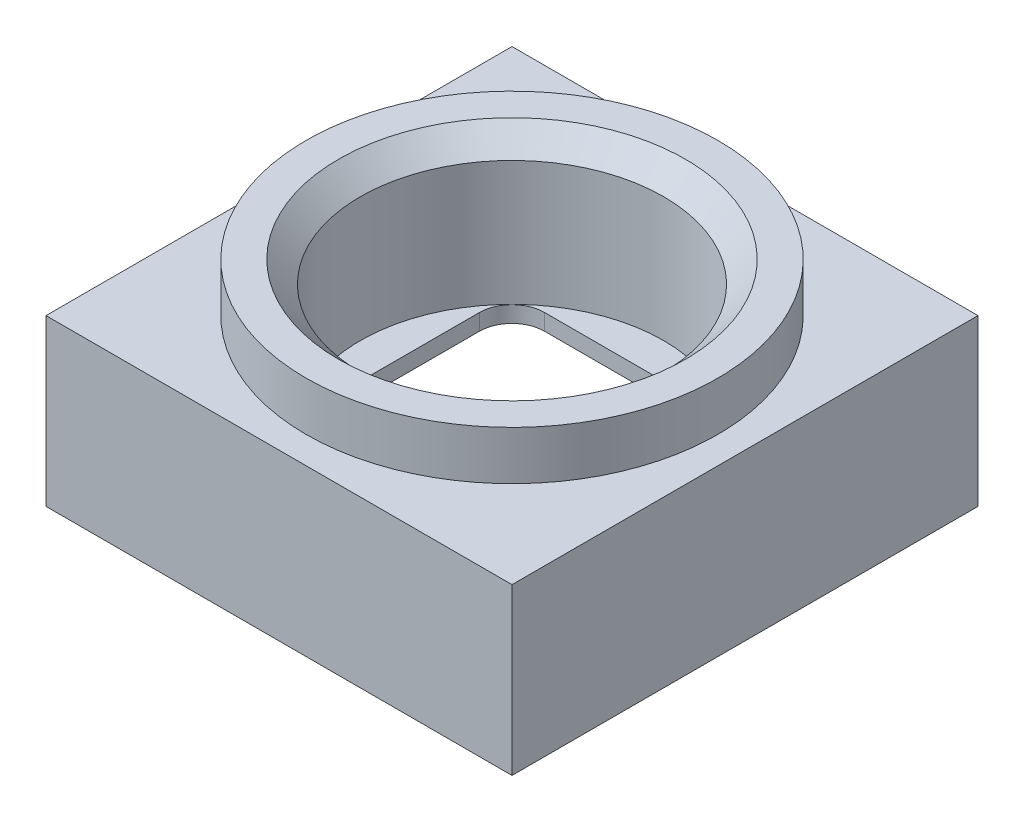
SolidWorks part; units mm, degrees
material "ABS PC"
ref_plane "Vorne" through (0, 0, 0) normal (0, 0, 1) x (1, 0, 0)
ref_plane "Oben" through (0, 0, 0) normal (0, 1, 0) x (1, 0, 0)
ref_plane "Rechts" through (0, 0, 0) normal (1, 0, 0) x (0, 0, -1)
sketch "downside" plane through (0, 0, 0) normal (0, 1, 0) x (1, 0, 0)
  line L0 (-4.3, 4.3) -> (4.3, -4.3) construction
  line L1 (-4.3, 4.3) -> (4.3, 4.3) construction
  line L2 (-4.3, 4.3) -> (-4.3, -4.3) construction
  line L3 (-4.3, -4.3) -> (4.3, -4.3) construction
  line L4 (4.3, 4.3) -> (4.3, -4.3) construction
  dimension "D1" = 8.6
sketch "Skizze2" plane through (0, 0, 0) normal (0, 1, 0) x (1, 0, 0)
  line L0 (-4.3, 4.3) -> (4.3, 4.3) construction
  line L1 (-4.3, 4.3) -> (-4.3, -4.3) construction
  line L2 (4.3, 4.3) -> (4.3, -4.3) construction
  line L3 (-4.3, -4.3) -> (4.3, -4.3) construction
  line L4 (-4.3, 4.3) -> (4.3, 4.3)
  line L5 (-4.3, 4.3) -> (-4.3, -4.3)
  line L6 (4.3, 4.3) -> (4.3, -4.3)
  line L7 (-4.3, -4.3) -> (4.3, -4.3)
  line L8 (-4, 4) -> (4, 4)
  line L9 (4, 4) -> (4, -4)
  line L10 (-4, -4) -> (4, -4)
  line L11 (-4, 4) -> (-4, -4)
  dimension "D1" = 0.3
extrude "Aufsatz-Linear austragen1" add sketch "Skizze2" along normal blind 0.6
sketch "Skizze5" plane through (0, 0.6, 0) normal (0, 1, 0) x (1, 0, 0)
  line L0 (0, 0) -> (0, 3.2) construction
  line L1 (-2.7646, 3.2) -> (2.7646, 3.2)
  line L2 (-2.7646, -3.2) -> (2.7646, -3.2)
  line L3 (-3.2, 2.7646) -> (-3.2, -2.7646)
  line L4 (3.2, 2.7646) -> (3.2, -2.7646)
  line L5 (0, 0) -> (3.2, 0) construction
  line L11 (-4.3, 4.3) -> (-4.3, -4.3)
  line L12 (-4.3, -4.3) -> (4.3, -4.3)
  line L13 (4.3, -4.3) -> (4.3, 4.3)
  line L14 (4.3, 4.3) -> (-4.3, 4.3)
  line L15 (-4.3, 4.3) -> (-4.3, -4.3)
  line L16 (-4.3, -4.3) -> (4.3, -4.3)
  line L17 (4.3, -4.3) -> (4.3, 4.3)
  line L18 (4.3, 4.3) -> (-4.3, 4.3)
  arc A0 (3.2, 2.7646) -> (2.7646, 3.2) centre (3.1, 3.1) ccw
  arc A1 (3.2, -2.7646) -> (2.7646, -3.2) centre (3.1, -3.1) cw
  arc A2 (-3.2, -2.7646) -> (-2.7646, -3.2) centre (-3.1, -3.1) ccw
  arc A3 (-3.2, 2.7646) -> (-2.7646, 3.2) centre (-3.1, 3.1) cw
  point P17 (0, -3.2)
  dimension "D1" = 0.7
  dimension "D2" = 6.4
  dimension "D3" = 0.1
  dimension "D4" = 0
extrude "Aufsatz-Linear austragen3" add sketch "Skizze5" along normal blind 0.35
sketch "Skizze4" plane through (0, 0.95, 0) normal (0, 1, 0) x (1, 0, 0)
  line L0 (0, 2.15) -> (0, -2.15) construction
  line L1 (-1.55, 2.15) -> (1.55, 2.15)
  line L2 (-2.15, 1.55) -> (-2.15, -1.55)
  line L3 (-1.55, -2.15) -> (1.55, -2.15)
  line L4 (2.15, 1.55) -> (2.15, -1.55)
  line L9 (4.3, 4.3) -> (-4.3, 4.3)
  line L10 (-4.3, 4.3) -> (-4.3, -4.3)
  line L11 (-4.3, -4.3) -> (4.3, -4.3)
  line L12 (4.3, -4.3) -> (4.3, 4.3)
  line L13 (4.3, 4.3) -> (-4.3, 4.3)
  line L14 (-4.3, 4.3) -> (-4.3, -4.3)
  line L15 (-4.3, -4.3) -> (4.3, -4.3)
  line L16 (4.3, -4.3) -> (4.3, 4.3)
  arc A0 (-2.15, -1.55) -> (-1.55, -2.15) centre (-1.55, -1.55) ccw
  arc A1 (1.55, -2.15) -> (2.15, -1.55) centre (1.55, -1.55) ccw
  arc A2 (1.55, 2.15) -> (2.15, 1.55) centre (1.55, 1.55) cw
  arc A3 (-1.55, 2.15) -> (-2.15, 1.55) centre (-1.55, 1.55) ccw
  dimension "D1" = 0.6
  dimension "D2" = 4.3
  dimension "D3" = 0
extrude "Aufsatz-Linear austragen2" add sketch "Skizze4" along normal blind 0.3
sketch "Skizze7" plane through (0, 1.25, 0) normal (0, 1, 0) x (1, 0, 0)
  line L4 (4.3, -4.3) -> (4.3, 4.3)
  line L5 (4.3, 4.3) -> (-4.3, 4.3)
  line L6 (-4.3, 4.3) -> (-4.3, -4.3)
  line L7 (-4.3, -4.3) -> (4.3, -4.3)
  line L8 (4.3, -4.3) -> (4.3, 4.3)
  line L9 (4.3, 4.3) -> (-4.3, 4.3)
  line L10 (-4.3, 4.3) -> (-4.3, -4.3)
  line L11 (-4.3, -4.3) -> (4.3, -4.3)
  circle A0 centre (0, 0) radius 2.8
  dimension "D2" = 5.6
  dimension "D1" = 0
extrude "Aufsatz-Linear austragen4" add sketch "Skizze7" along normal blind 1.8
cosmetic thread "Gewindedarstellung1" parameters "D1"=2.1, "D2"=6
sketch "Skizze8" plane through (0, 3.05, 0) normal (0, 1, 0) x (1, 0, 0)
  circle A0 centre (0, 0) radius 3.8
  circle A1 centre (0, 0) radius 2.8 construction
  circle A2 centre (0, 0) radius 2.8
  dimension "D1" = 7.6
extrude "Aufsatz-Linear austragen5" add sketch "Skizze8" along normal blind 0.9
chamfer "Fase1" distance 0.4 angle 45 1 edges at (0, 3.95, 2.8)
